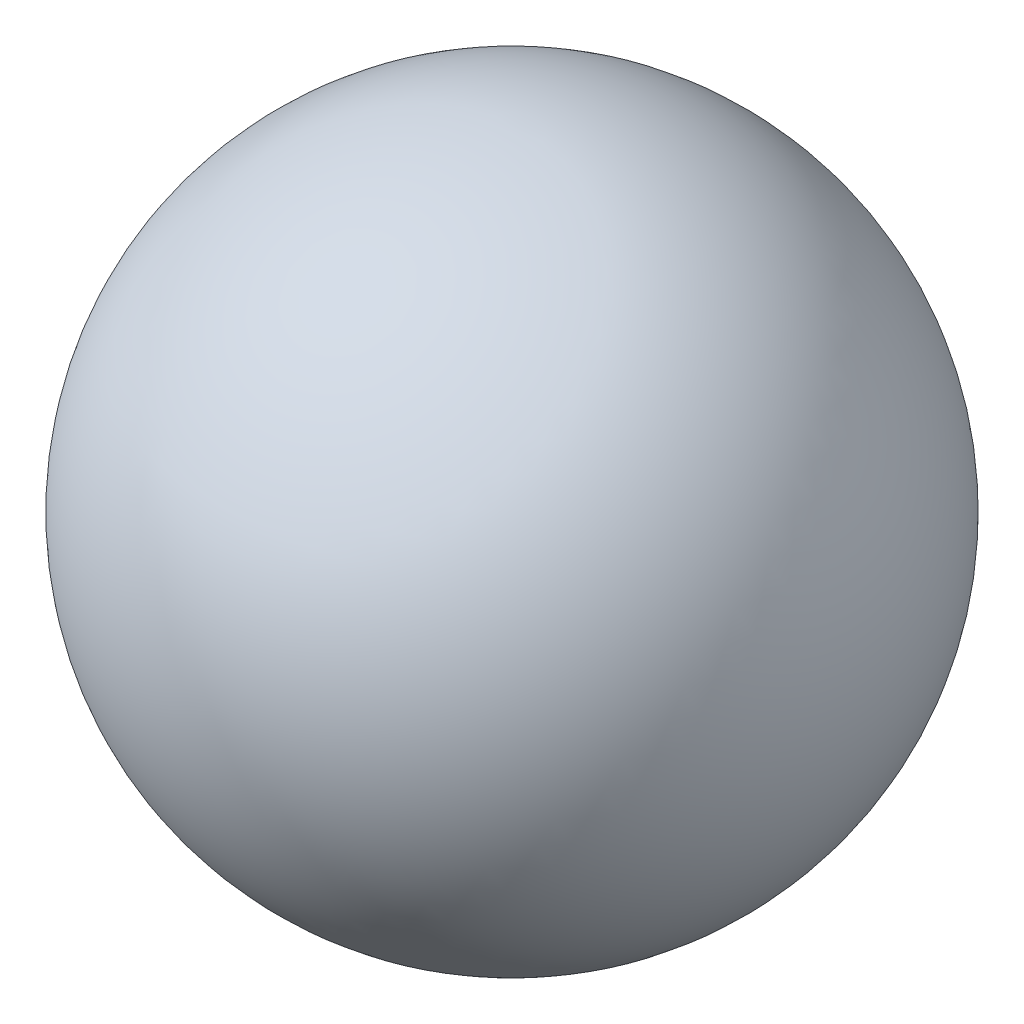
SolidWorks part; units mm, degrees
ref_plane "Front Plane" through (0, 0, 0) normal (0, 0, 1) x (1, 0, 0)
ref_plane "Top Plane" through (0, 0, 0) normal (0, 1, 0) x (1, 0, 0)
ref_plane "Right Plane" through (0, 0, 0) normal (1, 0, 0) x (0, 0, -1)
sketch "Sketch1" plane through (0, 0, 0) normal (1, 0, 0) x (0, 0, -1)
  line L0 (0, 18.415) -> (0, -18.415)
  arc A0 (0, -18.415) -> (0, 18.415) centre (0, 0) ccw
  dimension "D1" = 36.83
revolve "Revolve1" add sketch "Sketch1" angle 360 about L0
